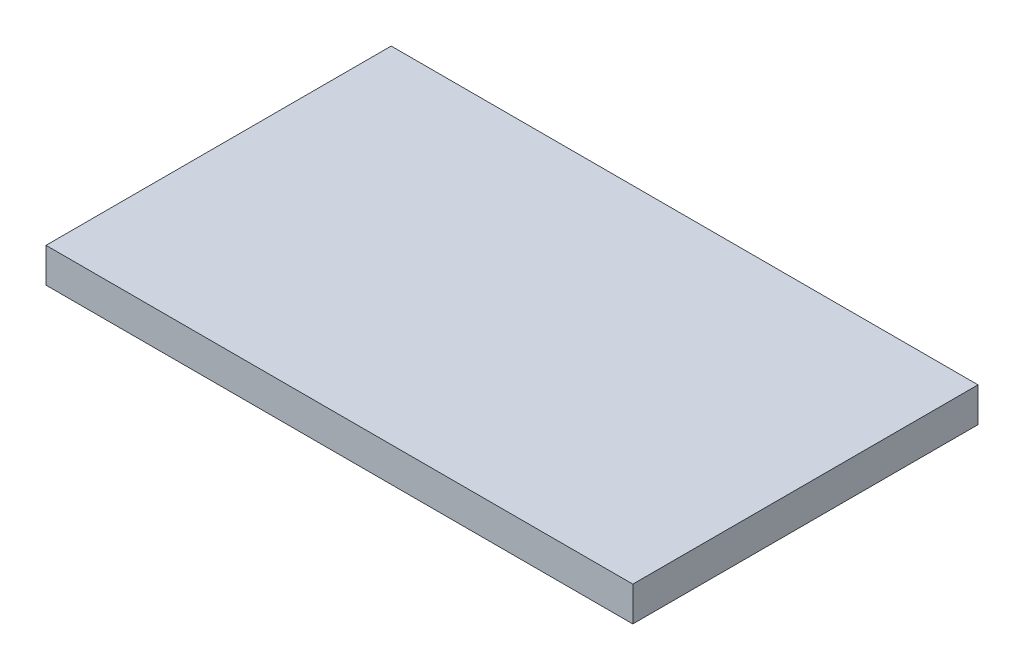
SolidWorks part; units mm, degrees
ref_plane "Front Plane" through (0, 0, 0) normal (0, 0, 1) x (1, 0, 0)
ref_plane "Top Plane" through (0, 0, 0) normal (0, 1, 0) x (1, 0, 0)
ref_plane "Right Plane" through (0, 0, 0) normal (1, 0, 0) x (0, 0, -1)
sketch "Sketch1" plane through (0, 0, 0) normal (0, 1, 0) x (1, 0, 0)
  line L1 (-85, -50) -> (85, -50)
  line L2 (-85, -50) -> (-85, 50)
  line L3 (-85, 50) -> (85, 50)
  line L4 (85, -50) -> (85, 50)
  line L5 (-85, -50) -> (85, 50) construction
  line L6 (-85, 50) -> (85, -50) construction
  point P0 (0, 0)
  dimension "D1" = 100
  dimension "D2" = 170
extrude "Boss-Extrude1" add sketch "Sketch1" along normal blind 10
